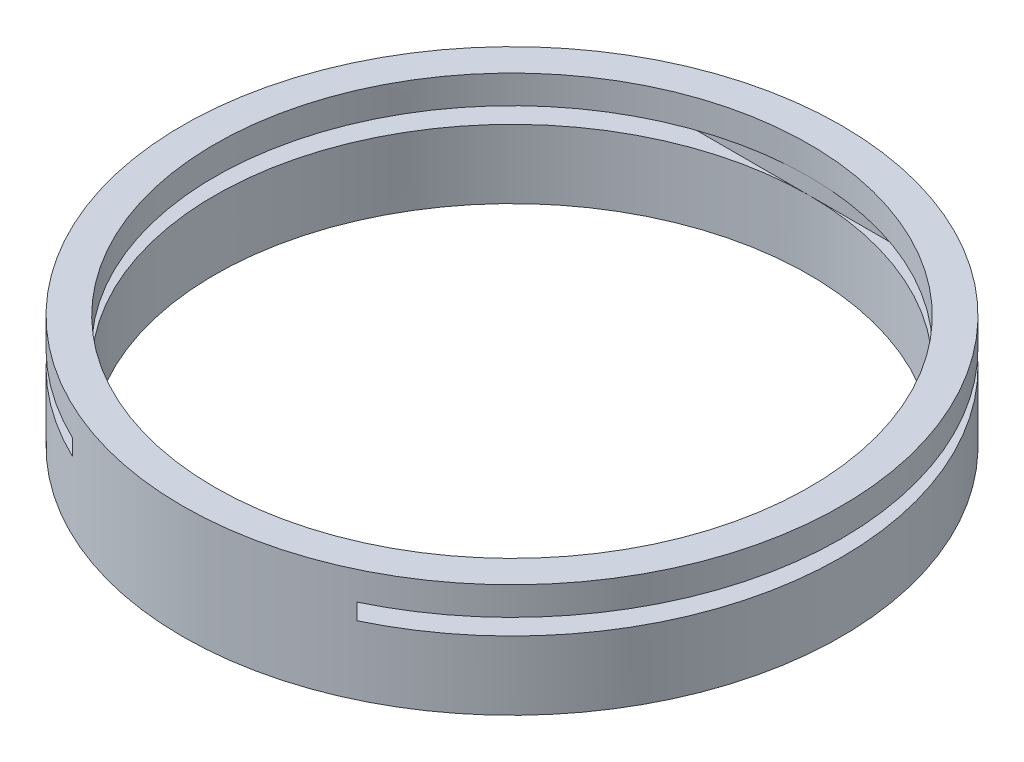
SolidWorks part; units mm, degrees
ref_plane "Front Plane" through (0, 0, 0) normal (0, 0, 1) x (1, 0, 0)
ref_plane "Top Plane" through (0, 0, 0) normal (0, 1, 0) x (1, 0, 0)
ref_plane "Right Plane" through (0, 0, 0) normal (1, 0, 0) x (0, 0, -1)
sketch "Sketch1" plane through (0, 0, 0) normal (0, 1, 0) x (1, 0, 0)
  circle A0 centre (0, 0) radius 18.4
  circle A1 centre (0, 0) radius 20.4
  dimension "D1" = 36.8
  dimension "D2" = 2
extrude "Boss-Extrude1" add sketch "Sketch1" along normal blind 7
sketch "Sketch5" plane through (0, 0, 0) normal (1, 0, 0) x (0, 0, -1)
  line L0 (0, 0) -> (0, 4) construction
  line L1 (0, 4) -> (0, 5.5) construction
  line L2 (20.4, 5.25) -> (18.4, 5.25) construction
  line L3 (-18.4, 4.25) -> (18.4, 4.25)
  line L4 (-18.4, 4.25) -> (-18.4, 5.25)
  line L5 (-18.4, 5.25) -> (18.4, 5.25)
  line L6 (18.4, 4.25) -> (18.4, 5.25)
  line L7 (-18.4, 4.25) -> (18.4, 5.25) construction
  line L8 (-18.4, 5.25) -> (18.4, 4.25) construction
  line L9 (20.4, 0) -> (20.4, 7) construction
  point P4 (0, 4.75)
  point P13 (0, 0)
  dimension "D1" = 4
  dimension "D2" = 1.5
  dimension "D3" = 2
  dimension "D4" = 1
extrude "Cut-Extrude1" cut sketch "Sketch5" against normal blind 29 and the other way blind 31 contours L4 L5 L6 L3
